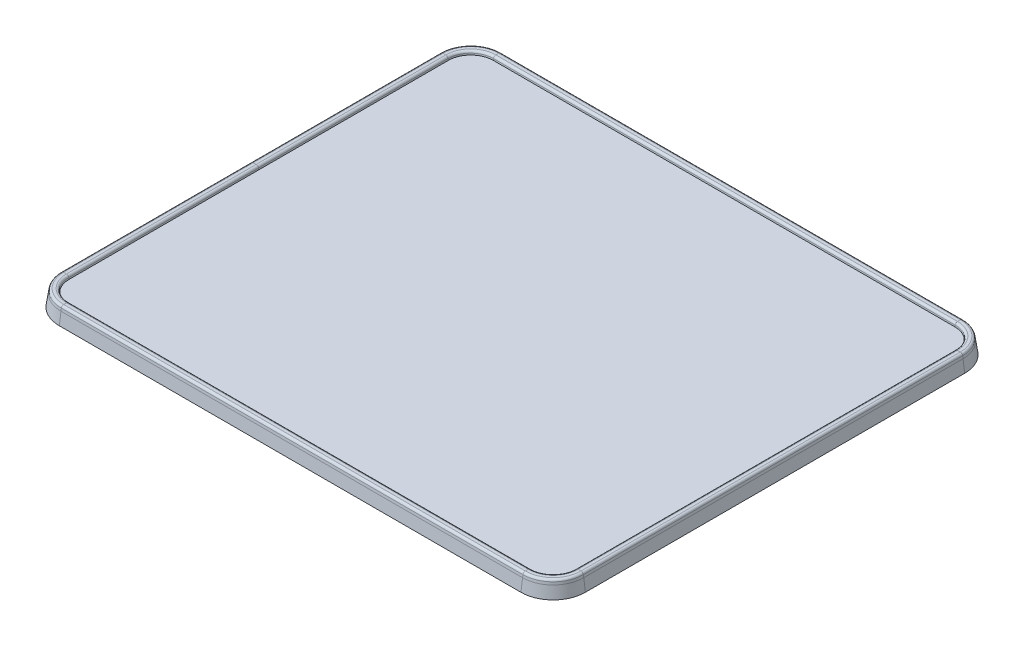
SolidWorks part; units mm, degrees
ref_plane "Front Plane" through (0, 0, 0) normal (0, 0, 1) x (1, 0, 0)
ref_plane "Top Plane" through (0, 0, 0) normal (0, 1, 0) x (1, 0, 0)
ref_plane "Right Plane" through (0, 0, 0) normal (1, 0, 0) x (0, 0, -1)
sketch "Sketch1" plane through (0, 0, 0) normal (0, 1, 0) x (1, 0, 0)
  line L1 (-187.325, -176.2125) -> (187.325, -176.2125)
  line L2 (-212.725, -150.8125) -> (-212.725, 150.8125)
  line L3 (-187.325, 176.2125) -> (187.325, 176.2125)
  line L4 (212.725, -150.8125) -> (212.725, 150.8125)
  line L5 (-212.725, -176.2125) -> (212.725, 176.2125) construction
  line L6 (-212.725, 176.2125) -> (212.725, -176.2125) construction
  arc A0 (-187.325, -176.2125) -> (-212.725, -150.8125) centre (-187.325, -150.8125) cw
  arc A1 (187.325, -176.2125) -> (212.725, -150.8125) centre (187.325, -150.8125) ccw
  arc A2 (212.725, 150.8125) -> (187.325, 176.2125) centre (187.325, 150.8125) ccw
  arc A3 (-187.325, 176.2125) -> (-212.725, 150.8125) centre (-187.325, 150.8125) ccw
  point P0 (0, 0)
  dimension "D3" = 25.4
  dimension "D1" = 425.45
  dimension "D2" = 352.425
ref_plane "Plane1" through (0, 428.625, 0) normal (0, 1, 0) x (1, 0, 0)
sketch "Sketch2" plane through (0, 428.625, 0) normal (0, 1, 0) x (1, 0, 0)
  line L1 (-255.5875, -236.5375) -> (255.5875, -236.5375)
  line L2 (-280.9875, -211.1375) -> (-280.9875, 211.1375)
  line L3 (-255.5875, 236.5375) -> (255.5875, 236.5375)
  line L4 (280.9875, -211.1375) -> (280.9875, 211.1375)
  line L5 (-280.9875, -236.5375) -> (280.9875, 236.5375) construction
  line L6 (-280.9875, 236.5375) -> (280.9875, -236.5375) construction
  line L7 (-249.2375, -230.1875) -> (249.2375, -230.1875)
  line L8 (-274.6375, -204.7875) -> (-274.6375, 204.7875)
  line L9 (-249.2375, 230.1875) -> (249.2375, 230.1875)
  line L10 (274.6375, -204.7875) -> (274.6375, 204.7875)
  line L11 (-274.6375, -230.1875) -> (274.6375, 230.1875) construction
  line L12 (-274.6375, 230.1875) -> (274.6375, -230.1875) construction
  arc A0 (-249.2375, -230.1875) -> (-274.6375, -204.7875) centre (-249.2375, -204.7875) cw
  arc A1 (249.2375, -230.1875) -> (274.6375, -204.7875) centre (249.2375, -204.7875) ccw
  arc A2 (274.6375, 204.7875) -> (249.2375, 230.1875) centre (249.2375, 204.7875) ccw
  arc A3 (-274.6375, 204.7875) -> (-249.2375, 230.1875) centre (-249.2375, 204.7875) cw
  arc A4 (280.9875, 211.1375) -> (255.5875, 236.5375) centre (255.5875, 211.1375) ccw
  arc A5 (280.9875, -211.1375) -> (255.5875, -236.5375) centre (255.5875, -211.1375) cw
  arc A6 (-255.5875, -236.5375) -> (-280.9875, -211.1375) centre (-255.5875, -211.1375) cw
  arc A7 (-280.9875, 211.1375) -> (-255.5875, 236.5375) centre (-255.5875, 211.1375) cw
  point P0 (0, 0)
  point P6 (0, 0)
  dimension "D5" = 25.4
  dimension "D6" = 25.4
  dimension "D1" = 473.075
  dimension "D2" = 561.975
  dimension "D3" = 460.375
  dimension "D4" = 549.275
sketch "Sketch3" plane through (0, 0, 0) normal (0, 0, 1) x (1, 0, 0)
  line L1 (-274.6375, 428.625) -> (-275.0265, 431.3183)
  line L2 (-276.2835, 432.4068) -> (-279.3415, 432.4068)
  line L3 (-280.5985, 431.3183) -> (-280.9875, 428.625)
  line L4 (-280.9875, 428.625) -> (280.9875, 428.625) construction
  line L5 (-280.9875, 428.625) -> (280.9875, 428.625) construction
  line L9 (-212.725, 0) -> (-274.6375, 428.625) construction
  line L13 (-273.5378, 429.895) -> (-273.7696, 431.4999)
  line L14 (-276.2835, 433.6768) -> (-279.3415, 433.6768)
  line L15 (-281.8554, 431.4999) -> (-282.2445, 428.8066)
  line L17 (-274.6375, 428.625) -> (-273.5378, 428.625)
  line L18 (-255.5875, 428.625) -> (-280.9875, 428.625) construction
  line L19 (-273.5378, 428.625) -> (-273.5378, 429.895)
  line L20 (-273.3805, 428.8066) -> (-273.7696, 431.4999) construction
  line L21 (-280.9875, 428.625) -> (-282.8219, 415.925)
  line L22 (-282.2445, 428.8066) -> (-284.0789, 416.1066)
  line L23 (-282.8219, 415.925) -> (-284.0789, 416.1066)
  arc A5 (-279.3415, 432.4068) -> (-280.5985, 431.3183) centre (-279.3415, 431.1368) ccw
  arc A6 (-275.0265, 431.3183) -> (-276.2835, 432.4068) centre (-276.2835, 431.1368) ccw
  arc A7 (-273.7696, 431.4999) -> (-276.2835, 433.6768) centre (-276.2835, 431.1368) ccw
  arc A8 (-279.3415, 433.6768) -> (-281.8554, 431.4999) centre (-279.3415, 431.1368) ccw
  dimension "D1" = 1.27
  dimension "D3" = 1.27
  dimension "D2" = 1.27
  dimension "D4" = 12.7
sketch "Sketch4" plane through (0, 0, 0) normal (0, 1, 0) x (1, 0, 0)
  line L4 (187.325, 176.2125) -> (-187.325, 176.2125)
  line L5 (212.725, -150.8125) -> (212.725, 150.8125)
  line L6 (-187.325, -176.2125) -> (187.325, -176.2125)
  line L7 (-212.725, 150.8125) -> (-212.725, -150.8125)
  line L8 (187.325, 176.2125) -> (-187.325, 176.2125)
  line L9 (212.725, -150.8125) -> (212.725, 150.8125)
  line L10 (-187.325, -176.2125) -> (187.325, -176.2125)
  line L11 (-212.725, 150.8125) -> (-212.725, -150.8125)
  arc A4 (-187.325, 176.2125) -> (-212.725, 150.8125) centre (-187.325, 150.8125) ccw
  arc A5 (212.725, 150.8125) -> (187.325, 176.2125) centre (187.325, 150.8125) ccw
  arc A6 (187.325, -176.2125) -> (212.725, -150.8125) centre (187.325, -150.8125) ccw
  arc A7 (-212.725, -150.8125) -> (-187.325, -176.2125) centre (-187.325, -150.8125) ccw
  arc A8 (-187.325, 176.2125) -> (-212.725, 150.8125) centre (-187.325, 150.8125) ccw
  arc A9 (212.725, 150.8125) -> (187.325, 176.2125) centre (187.325, 150.8125) ccw
  arc A10 (187.325, -176.2125) -> (212.725, -150.8125) centre (187.325, -150.8125) ccw
  arc A11 (-212.725, -150.8125) -> (-187.325, -176.2125) centre (-187.325, -150.8125) ccw
  dimension "D1" = 0
sweep "Sweep1" add profiles "Sketch3" path "Sketch2"
sketch "Sketch6" plane through (0, 428.625, 0) normal (0, 1, 0) x (1, 0, 0)
  line L0 (249.2375, 229.0878) -> (-249.2375, 229.0878) construction
  line L1 (-273.5378, 0) -> (-273.5378, -204.7875) construction
  line L2 (-249.2375, -229.0878) -> (249.2375, -229.0878) construction
  line L3 (273.5378, -204.7875) -> (273.5378, 204.7875) construction
  line L4 (249.2375, 229.0878) -> (-249.2375, 229.0878)
  line L5 (-273.5378, 0) -> (-273.5378, -204.7875)
  line L6 (-249.2375, -229.0878) -> (249.2375, -229.0878)
  line L7 (273.5378, -204.7875) -> (273.5378, 204.7875)
  line L8 (-273.5378, 204.7875) -> (-273.5378, 0) construction
  line L9 (-273.5378, 204.7875) -> (-273.5378, 0)
  arc A1 (-273.5378, -204.7875) -> (-249.2375, -229.0878) centre (-249.2375, -204.7875) ccw construction
  arc A2 (-273.5378, -204.7875) -> (-249.2375, -229.0878) centre (-249.2375, -204.7875) ccw
  arc A3 (249.2375, -229.0878) -> (273.5378, -204.7875) centre (249.2375, -204.7875) ccw construction
  arc A4 (249.2375, -229.0878) -> (273.5378, -204.7875) centre (249.2375, -204.7875) ccw
  arc A5 (273.5378, 204.7875) -> (249.2375, 229.0878) centre (249.2375, 204.7875) ccw construction
  arc A6 (273.5378, 204.7875) -> (249.2375, 229.0878) centre (249.2375, 204.7875) ccw
  arc A7 (-249.2375, 229.0878) -> (-273.5378, 204.7875) centre (-249.2375, 204.7875) ccw construction
  arc A8 (-249.2375, 229.0878) -> (-273.5378, 204.7875) centre (-249.2375, 204.7875) ccw
extrude "Boss-Extrude1" add sketch "Sketch6" along normal blind 1.27
